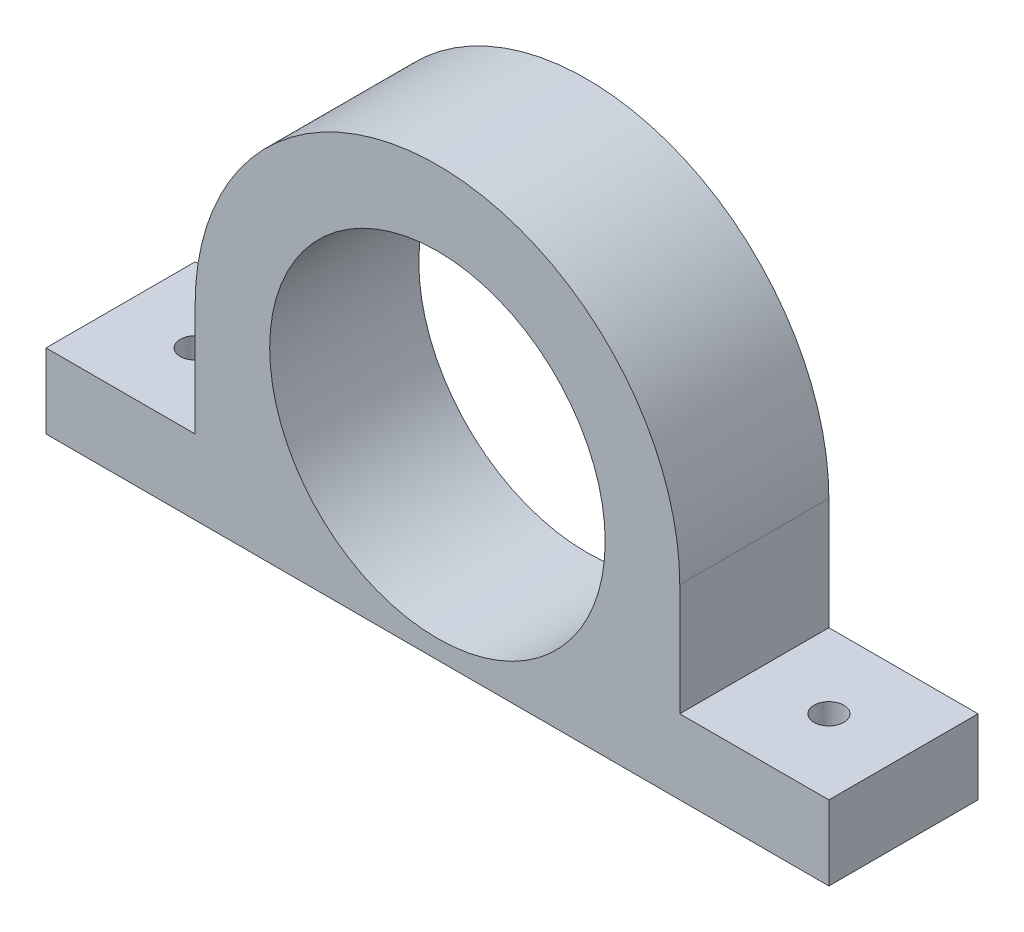
SolidWorks part; units mm, degrees
ref_plane "Front Plane" through (0, 0, 0) normal (0, 0, 1) x (1, 0, 0)
ref_plane "Top Plane" through (0, 0, 0) normal (0, 1, 0) x (1, 0, 0)
ref_plane "Right Plane" through (0, 0, 0) normal (1, 0, 0) x (0, 0, -1)
sketch "Sketch1" plane through (0, 0, -167.5) normal (0, 0, 1) x (1, 0, 0)
  line L0 (-32.5, 0) -> (-32.5, -15)
  line L1 (-32.5, -15) -> (-52.5, -15)
  line L2 (-52.5, -15) -> (-52.5, -25)
  line L4 (-52.5, -25) -> (52.5, -25)
  line L5 (52.5, -25) -> (52.5, -15)
  line L6 (52.5, -15) -> (32.5, -15)
  line L7 (32.5, -15) -> (32.5, 0)
  arc A2 (-32.5, 0) -> (32.5, 0) centre (0, 0) cw
  circle A3 centre (0, 0) radius 22.5
  point P1 (79.019, 171.914)
  point P2 (0, 0)
  point P8 (-2.5, 90.7303)
  point P9 (102.5, 90.8696)
  point P12 (60.721, 91.3986)
  point P13 (0, 0)
  point P15 (0, 0)
  point P16 (0, 32.5)
  dimension "D3" = 10
  dimension "D2" = 45
  dimension "D1" = 10
  dimension "D4" = 20
  dimension "D5" = 2.5
extrude "Boss-Extrude2" add sketch "Sketch1" against normal blind 20
hole_wizard "Ø4.0mm Dowel Hole1" positions "Sketch2" profile "Sketch4" hole size "Ø4.0" standard "ANSI Metric" end condition through all
sketch "Sketch2" plane through (0, -15, 0) normal (0, 1, 0) x (1, 0, 0)
  line L0 (52.5, 187.5) -> (52.5, 167.5) construction
  line L1 (52.5, 187.5) -> (32.5, 187.5) construction
  line L2 (-52.5, 187.5) -> (-52.5, 167.5) construction
  line L3 (-32.5, 187.5) -> (-52.5, 187.5) construction
  point P0 (42.5, 177.5)
  point P2 (-42.5, 177.5)
  dimension "D1" = 10
  dimension "D2" = 10
  dimension "D3" = 10
  dimension "D4" = 10
sketch "Sketch4" plane through (42.5, -15, -177.5) normal (1, 0, 0) x (0, 0, 1)
  line L0 (0, 0) -> (0, 10)
  line L1 (0, 10) -> (2, 10)
  line L2 (2, 10) -> (2, 0)
  line L5 (2, 0) -> (0, 0)
  line L11 (0, -6.35) -> (0, 107.95) construction
  dimension "Thru Hole Dia." = 4
  dimension "Thru Hole Depth" = 10
